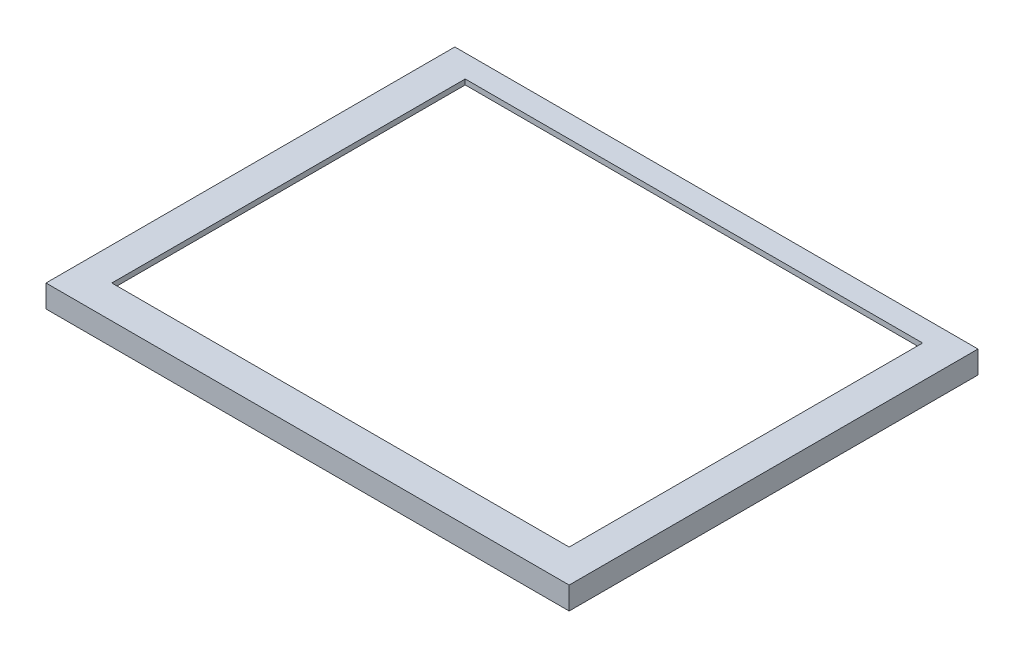
SolidWorks part; units mm, degrees
ref_plane "前视" through (0, 0, 0) normal (0, 0, 1) x (1, 0, 0)
ref_plane "上视" through (0, 0, 0) normal (0, 1, 0) x (1, 0, 0)
ref_plane "右视" through (0, 0, 0) normal (1, 0, 0) x (0, 0, -1)
sketch "Sketch1" plane through (0, 0, 0) normal (0, 1, 0) x (1, 0, 0)
  line L0 (-75.5, 59) -> (75.5, 59)
  line L1 (-74, -57.5) -> (74, -57.5)
  line L2 (-74, -57.5) -> (-74, 57.5)
  line L3 (-74, 57.5) -> (74, 57.5)
  line L4 (74, -57.5) -> (74, 57.5)
  line L5 (-74, -57.5) -> (74, 57.5) construction
  line L6 (-74, 57.5) -> (74, -57.5) construction
  line L7 (75.5, -59) -> (75.5, 59)
  line L8 (-75.5, -59) -> (75.5, -59)
  line L9 (-75.5, -59) -> (-75.5, 59)
  point P0 (0, 0)
  dimension "D1" = 148
  dimension "D2" = 115
  dimension "D3" = 1.5
extrude "Boss-Extrude1" add sketch "Sketch1" along normal blind 5
sketch "Sketch2" plane through (0, 5, 0) normal (0, 1, 0) x (1, 0, 0)
  line L1 (-75.5, 59) -> (75.5, 59)
  line L2 (-75.5, 59) -> (-75.5, -59)
  line L3 (-75.5, -59) -> (75.5, -59)
  line L4 (75.5, 59) -> (75.5, -59)
  line L5 (-74, 57.5) -> (74, 57.5) construction
  line L6 (-74, 57.5) -> (-74, -57.5) construction
  line L7 (-74, -57.5) -> (74, -57.5) construction
  line L8 (74, 57.5) -> (74, -57.5) construction
  line L9 (-66, 52.5) -> (66, 52.5)
  line L10 (-66, 52.5) -> (-66, -49.5)
  line L11 (-66, -49.5) -> (66, -49.5)
  line L12 (66, 52.5) -> (66, -49.5)
  dimension "D1" = 5
  dimension "D2" = 8
  dimension "D3" = 8
  dimension "D4" = 8
extrude "Boss-Extrude2" add sketch "Sketch2" along normal blind 1.5
